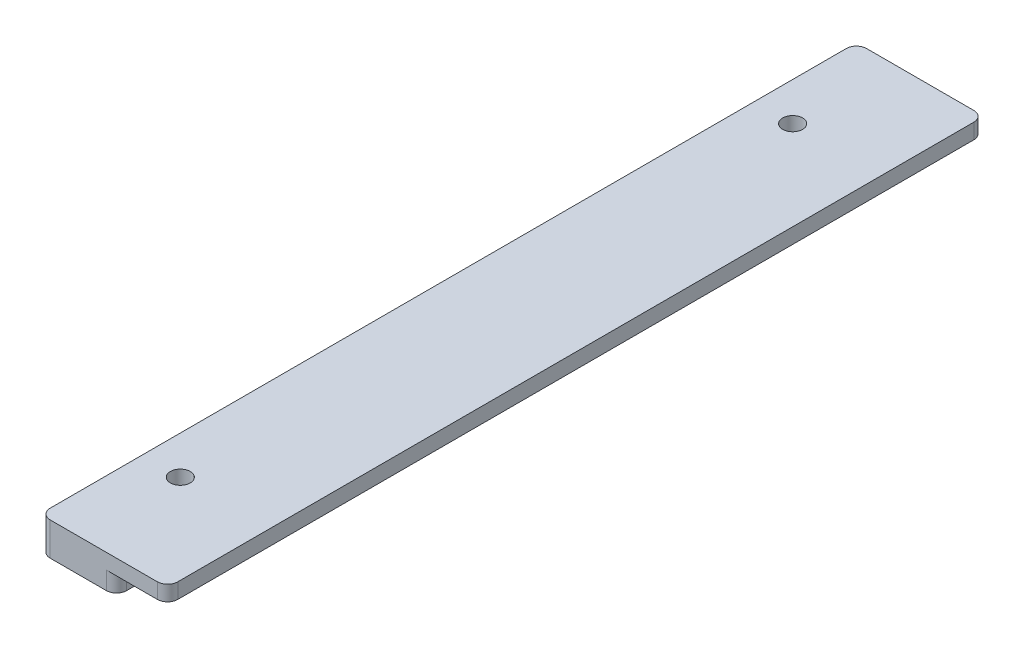
SolidWorks part; units mm, degrees
ref_plane "前视基准面" through (0, 0, 0) normal (0, 0, 1) x (1, 0, 0)
ref_plane "上视基准面" through (0, 0, 0) normal (0, 1, 0) x (1, 0, 0)
ref_plane "右视基准面" through (0, 0, 0) normal (1, 0, 0) x (0, 0, -1)
sketch "草图1" plane through (0, 0, 0) normal (0, 0, 1) x (1, 0, 0)
  line L0 (0, 0) -> (0, 6.5)
  line L1 (0, 6.5) -> (25, 6.5)
  line L2 (25, 6.5) -> (25, 3.5)
  line L3 (25, 3.5) -> (15, 3.5)
  line L4 (15, 3.5) -> (15, 0)
  line L5 (15, 0) -> (0, 0)
  dimension "D1" = 15
  dimension "D2" = 3
  dimension "D3" = 3.5
  dimension "D4" = 10
extrude "凸台-拉伸1" add sketch "草图1" along normal blind 160
sketch "草图2" plane through (0, 0, 0) normal (0, -1, 0) x (1, 0, 0)
  line L0 (7.5, 0) -> (7.5, 160) construction
  line L1 (0, 0) -> (15, 0) construction
  line L2 (0, 160) -> (15, 160) construction
  circle A0 centre (7.5, 80) radius 1.95 construction
  circle A1 centre (7.5, 140) radius 1.95
  circle A2 centre (7.5, 20) radius 1.95
  dimension "D3" = 3.9
  dimension "D1" = 60
  dimension "D2" = 60
extrude "切除-拉伸1" cut sketch "草图2" against normal up to next
fillet "圆角1" radius 2 6 edges at (15, 1.75, 0) (15, 1.75, 160) (25, 5, 160) (0, 3.25, 160) (25, 5, 0) (0, 3.25, 0)
